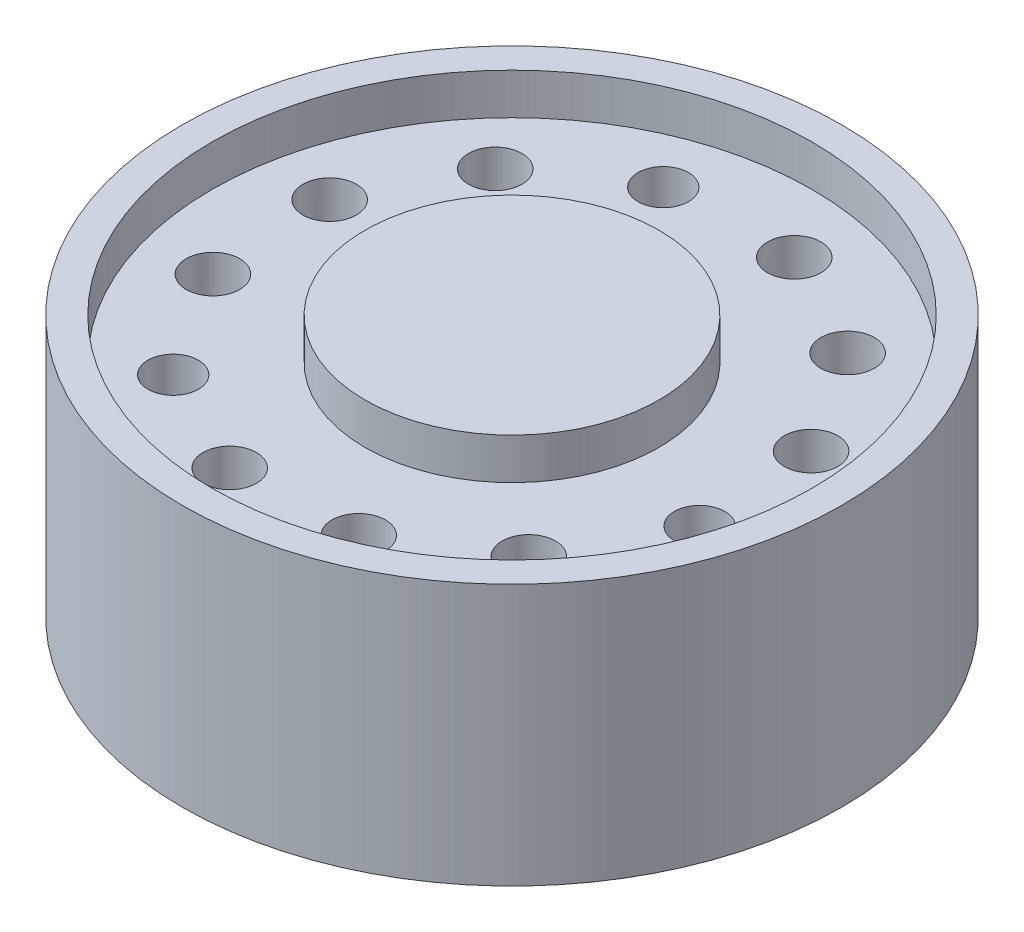
SolidWorks part; units mm, degrees
ref_plane "Alzado" through (0, 0, 0) normal (0, 0, 1) x (1, 0, 0)
ref_plane "Planta" through (0, 0, 0) normal (0, 1, 0) x (1, 0, 0)
ref_plane "Vista lateral" through (0, 0, 0) normal (1, 0, 0) x (0, 0, -1)
sketch "Croquis1" plane through (0, 0, 0) normal (0, 1, 0) x (1, 0, 0)
  circle A0 centre (0, 0) radius 55.5
  dimension "D1" = 111
extrude "Saliente-Extruir1" add sketch "Croquis1" along normal blind 44
sketch "Croquis2" plane through (0, 44, 0) normal (0, 1, 0) x (1, 0, 0)
  circle A0 centre (0, 0) radius 50.5
  circle A1 centre (0, 0) radius 24.75
  dimension "D1" = 101
  dimension "D2" = 49.5
extrude "Cortar-Extruir2" cut sketch "Croquis2" against normal blind 6.93 contours A0 A1
hole_wizard "Refrentado para tornillo con cabeza troncocónica de M81" positions "Croquis6" profile "Croquis5" counterbore size "M8" standard "Ansi Metric"
sketch "Croquis6" plane through (0, 0, 0) normal (0, -1, 0) x (-1, 0, 0)
  line L0 (8.41, -39.1059) -> (0, 0) construction
  point P0 (8.41, -39.1059)
  point P12 (-12.2697, -38.0717)
  point P13 (-29.6617, -26.8362)
  point P16 (-38.0717, 12.2697)
  point P17 (-26.8362, 29.6617)
  point P18 (-8.41, 39.1059)
  point P20 (29.6617, 26.8362)
  point P21 (39.1059, 8.41)
  point P22 (38.0717, -12.2697)
  point P24 (26.8362, -29.6617) [skipped]
  point P25 (-39.1059, -8.41) [skipped]
  point P26 (12.2697, 38.0717) [skipped]
  dimension "D1" = 40
  dimension "D2" = 12
sketch "Croquis5" plane through (-8.41, 0, 39.1059) normal (1, 0, 0) x (0, 0, -1)
  line L0 (0, 0) -> (0, 37.07)
  line L1 (0, 37.07) -> (4.5, 37.07)
  line L3 (4.5, 37.07) -> (4.5, 30)
  line L4 (4.5, 30) -> (9, 30)
  line L5 (9, 30) -> (9, 0)
  line L7 (9, 0) -> (0, 0)
  line L11 (0, -6.35) -> (0, 107.95) construction
  dimension "Diámetro de taladro hasta el siguiente" = 9
  dimension "Profundidad de taladro hasta el siguiente" = 37.07
  dimension "Diámetro de refrentado" = 18
  dimension "Profundidad de refrentado" = 30
hole_wizard "Taladro roscado M10x1.51" positions "Croquis8" profile "Croquis7" tap size "M10x1.5" standard "Ansi Metric" end condition up to next
sketch "Croquis8" plane through (0, 0, 0) normal (0, -1, 0) x (-1, 0, 0)
  line L0 (26.7551, -30.2842) -> (0, 0) construction
  point P0 (26.7551, -30.2842)
  point P11 (-39.6044, -8.0286)
  point P12 (12.8493, 38.3127)
  dimension "D1" = 40.41
  dimension "D2" = 3
sketch "Croquis7" plane through (-26.7551, 0, 30.2842) normal (1, 0, 0) x (0, 0, -1)
  line L0 (0, 0) -> (0, 37.07)
  line L1 (0, 37.07) -> (4.25, 37.07)
  line L2 (4.25, 37.07) -> (4.25, 0)
  line L5 (4.25, 0) -> (0, 0)
  line L11 (0, -6.35) -> (0, 107.95) construction
  dimension "Diámetro de perforador para roscar hasta el siguiente" = 8.5
  dimension "Profundidad de perforador para roscar hasta el siguiente" = 37.07
cosmetic thread "Rosca de taladro1"
cosmetic thread "Rosca de taladro2"
cosmetic thread "Rosca de taladro3"
